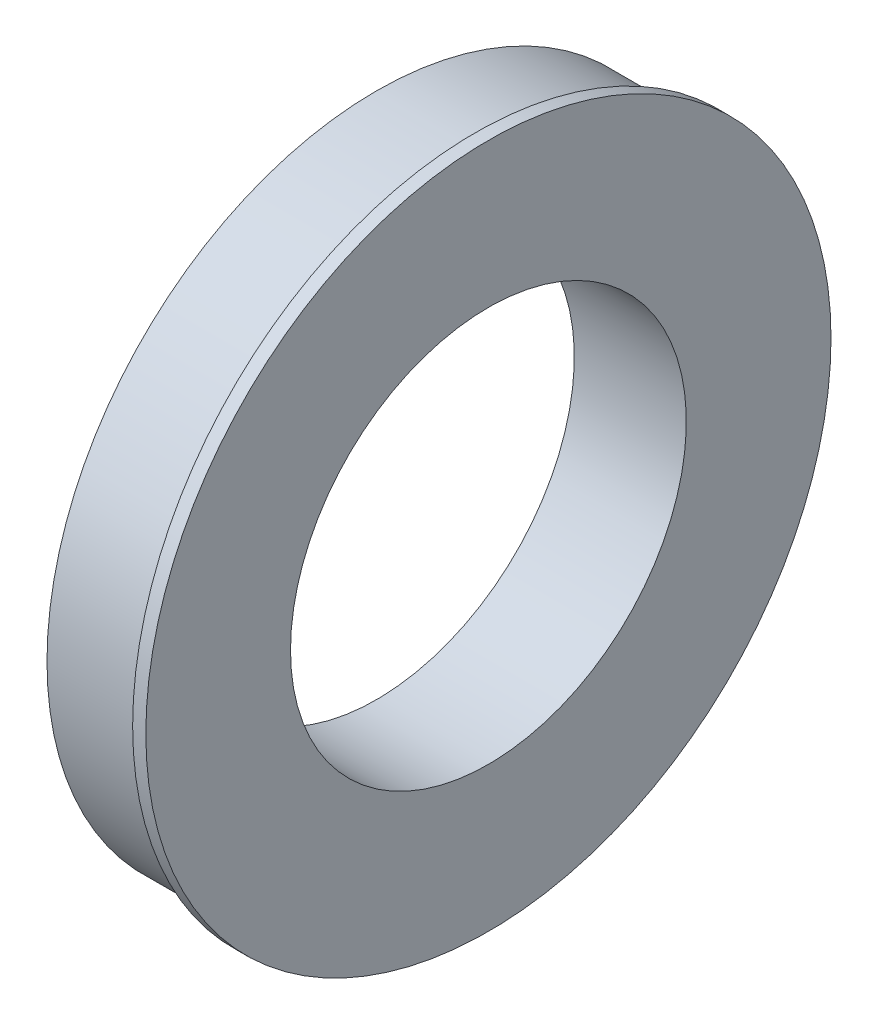
SolidWorks part; units mm, degrees
ref_plane "Front Plane" through (0, 0, 0) normal (0, 0, 1) x (1, 0, 0)
ref_plane "Top Plane" through (0, 0, 0) normal (0, 1, 0) x (1, 0, 0)
ref_plane "Right Plane" through (0, 0, 0) normal (1, 0, 0) x (0, 0, -1)
sketch "Sketch2" plane through (0, 0, 0) normal (1, 0, 0) x (0, 0, -1)
  circle A0 centre (0, 0) radius 38.15
  circle A1 centre (0, 0) radius 63.5
  dimension "D1" = 127
  dimension "D2" = 76.3
extrude "Boss-Extrude1" add sketch "Sketch2" along normal blind 19.05
sketch "Sketch3" plane through (19.05, 0, 0) normal (1, 0, 0) x (0, 0, -1)
  circle A2 centre (0, 0) radius 38.15 construction
  circle A3 centre (0, 0) radius 66.04
  circle A4 centre (0, 0) radius 66.04
  circle A5 centre (0, 0) radius 38.15
  dimension "D1" = 2.54
extrude "Boss-Extrude4" add sketch "Sketch3" along normal blind 2.54
